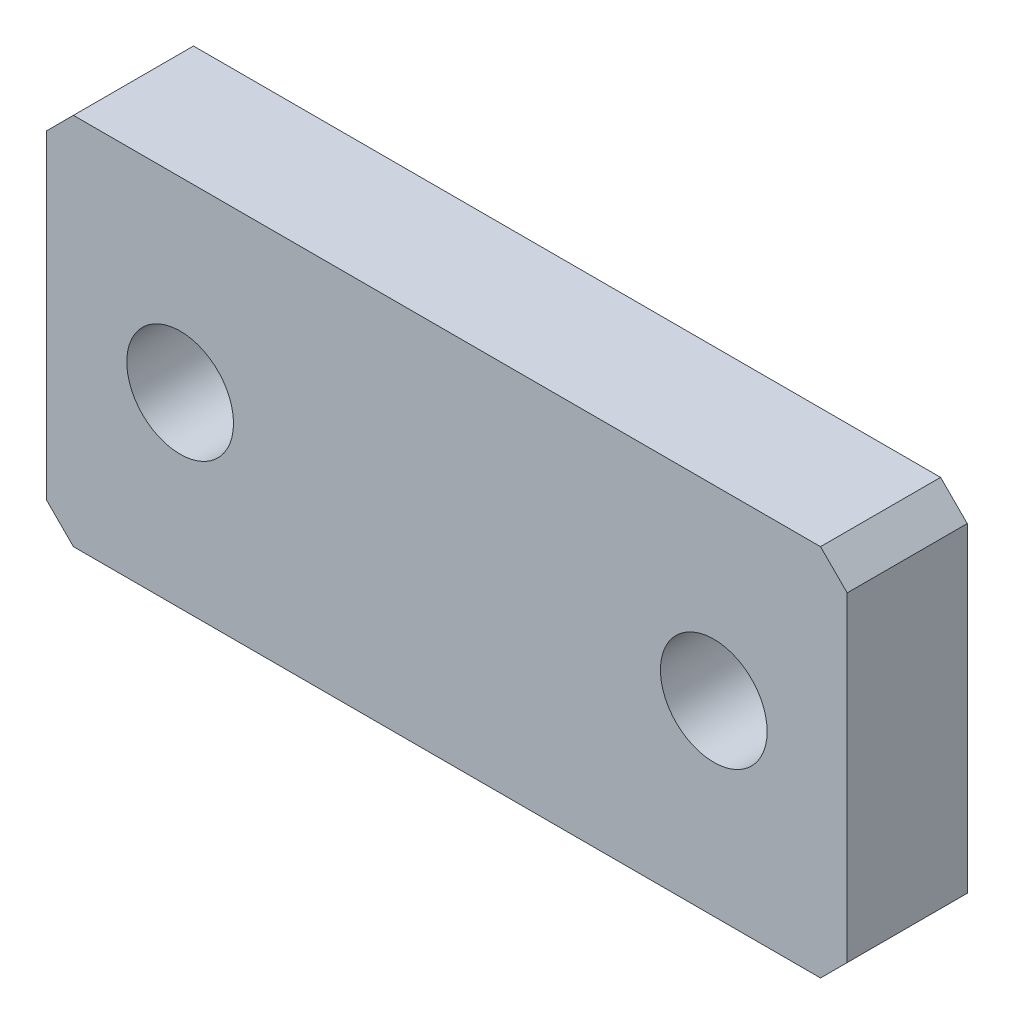
SolidWorks part; units mm, degrees
ref_plane "前视基准面" through (0, 0, 0) normal (0, 0, 1) x (1, 0, 0)
ref_plane "上视基准面" through (0, 0, 0) normal (0, 1, 0) x (1, 0, 0)
ref_plane "右视基准面" through (0, 0, 0) normal (1, 0, 0) x (0, 0, -1)
sketch "草图1" plane through (0, 0, 0) normal (0, 0, 1) x (1, 0, 0)
  line L52 (1281.3228, 1001.2564) -> (1253.3228, 1001.2564)
  line L53 (1282.3228, 1000.2564) -> (1281.3228, 1001.2564)
  line L54 (1252.3228, 1000.2564) -> (1253.3228, 1001.2564)
  line L55 (1281.3228, 987.2564) -> (1253.3228, 987.2564)
  line L56 (1282.3228, 988.2564) -> (1282.3228, 1000.2564)
  line L57 (1281.3228, 987.2564) -> (1282.3228, 988.2564)
  line L58 (1252.3228, 988.2564) -> (1252.3228, 1000.2564)
  line L59 (1253.3228, 987.2564) -> (1252.3228, 988.2564)
  line L60 (1253.7282, 994.2564) -> (1261.2188, 994.2564) construction
  line L61 (1257.3228, 997.6657) -> (1257.3228, 990.7729) construction
  line L62 (1273.7282, 994.2564) -> (1281.2188, 994.2564) construction
  line L63 (1277.3228, 997.6657) -> (1277.3228, 990.7729) construction
  circle A5 centre (1257.3228, 994.2564) radius 2
  circle A7 centre (1277.3228, 994.2564) radius 2
extrude "拉伸1" add sketch "草图1" along normal blind 4.5
